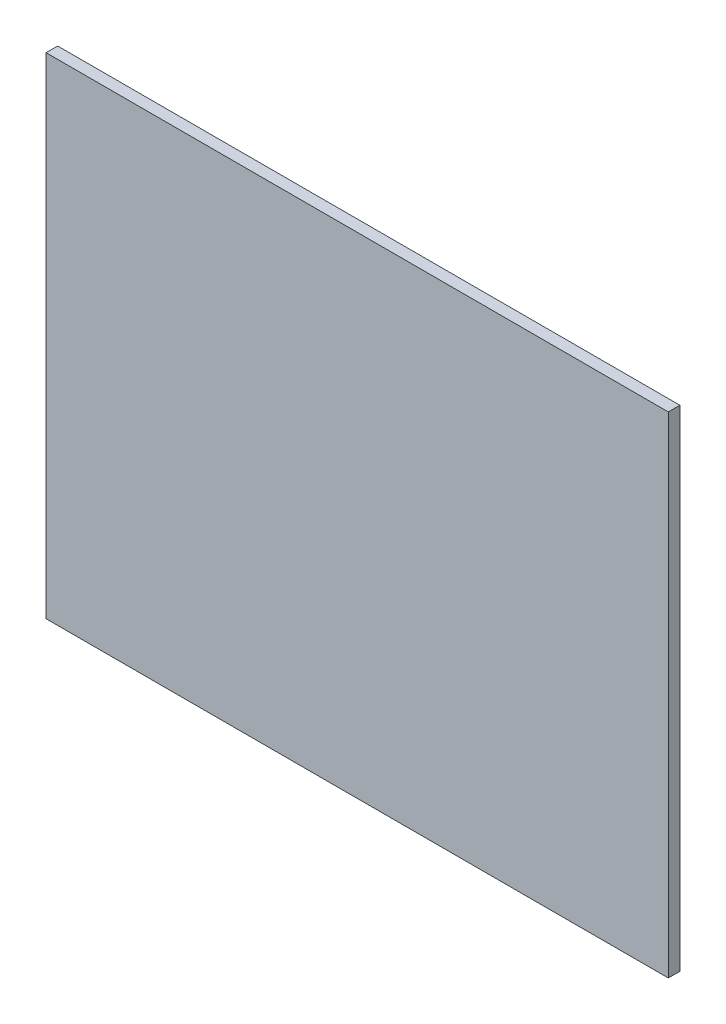
SolidWorks part; units mm, degrees
ref_plane "Спереди" through (0, 0, 0) normal (0, 0, 1) x (1, 0, 0)
ref_plane "Сверху" through (0, 0, 0) normal (0, 1, 0) x (1, 0, 0)
ref_plane "Справа" through (0, 0, 0) normal (1, 0, 0) x (0, 0, -1)
sketch "Эскиз1" plane through (0, 0, 0) normal (0, 0, 1) x (1, 0, 0)
  line L5 (19.4, 16.9) -> (19.4, -16.9)
  line L6 (23.4, 17) -> (23.4, 14.8) construction
  line L14 (23.3, -14.8) -> (23.3, -16.9)
  line L15 (23.3, -16.9) -> (-23.5, -16.9)
  line L16 (-23.5, -16.9) -> (-23.5, 16.9)
  line L17 (-23.5, 16.9) -> (23.4, 16.9)
  line L19 (19.4, -16.9) -> (-23.5, -16.9)
  line L20 (-23.5, -16.9) -> (-23.5, 16.9)
  line L21 (-23.5, 16.9) -> (19.4, 16.9)
  dimension "D1" = 0.1
  dimension "D2" = 4
  dimension "D3" = 33.8
  dimension "D4" = 42.9
extrude "Бобышка-Вытянуть1" add sketch "Эскиз1" along normal blind 0.8 from offset 0.8
